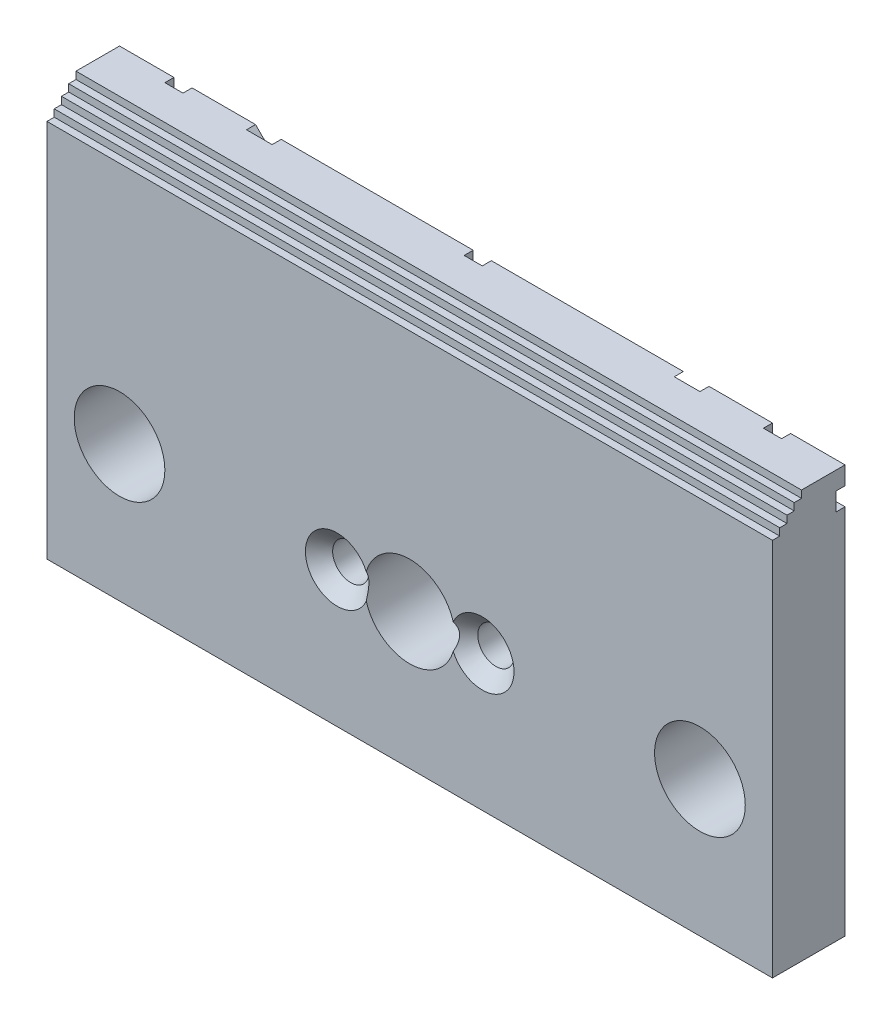
SolidWorks part; units mm, degrees
ref_plane "前视基准面" through (0, 0, 0) normal (0, 0, 1) x (1, 0, 0)
ref_plane "上视基准面" through (0, 0, 0) normal (0, 1, 0) x (1, 0, 0)
ref_plane "右视基准面" through (0, 0, 0) normal (1, 0, 0) x (0, 0, -1)
other "Configuration Table"
ref_plane "基准面1" through (0, 0, 1) normal (0, 0, -1) x (-1, 0, 0)
sketch "草图1" plane through (0, 0, 1) normal (0, 0, -1) x (-1, 0, 0)
  line L0 (-80, -13.3333) -> (0, -13.3333)
  line L1 (0, -13.3333) -> (0, 46.6667)
  line L2 (0, 46.6667) -> (-80, 46.6667)
  line L3 (-80, 46.6667) -> (-80, -13.3333)
  dimension "D1" = 80
  dimension "D2" = 60
extrude "凸台-拉伸1" add sketch "草图1" against normal blind 8
hole_wizard "Ø10.0 (10) 直径孔1" positions "草图21" profile "草图20" hole size "Ø10.0" standard "ANSI Metric" end condition through all
sketch "草图21" plane through (0, 0, 9) normal (0, 0, 1) x (1, 0, 0)
  line L0 (80, 16.6667) -> (0, 16.6667) construction
  line L1 (80, 46.6667) -> (80, -13.3333) construction
  line L2 (0, -13.3333) -> (0, 46.6667) construction
  line L3 (0, 46.6667) -> (80, 46.6667) construction
  point P0 (72, 16.6667)
  point P1 (8, 16.6667)
  dimension "D1" = 8
  dimension "D2" = 8
  dimension "D3" = 30
sketch "草图20" plane through (72, 16.6667, 9) normal (1, 0, 0) x (0, -1, 0)
  line L0 (0, 0) -> (0, 8)
  line L1 (0, 8) -> (5, 8)
  line L2 (5, 8) -> (5, 0)
  line L5 (5, 0) -> (0, 0)
  line L11 (0, -6.35) -> (0, 107.95) construction
  dimension "通孔孔直径" = 10
  dimension "通孔孔深度" = 8
hole_wizard "Ø10.0 (10) 直径孔2" positions "草图23" profile "草图22" hole size "Ø10.0" standard "ANSI Metric" end condition through all
sketch "草图23" plane through (0, 0, 1) normal (0, 0, -1) x (-1, 0, 0)
  line L0 (-80, 16.6667) -> (0, 16.6667) construction
  line L3 (0, 46.6667) -> (-80, 46.6667) construction
  point P0 (-40, 16.6667)
  dimension "D1" = 30
sketch "草图22" plane through (40, 16.6667, 1) normal (1, 0, 0) x (0, 1, 0)
  line L0 (0, 0) -> (0, 8)
  line L1 (0, 8) -> (5, 8)
  line L2 (5, 8) -> (5, 0)
  line L5 (5, 0) -> (0, 0)
  line L11 (0, -6.35) -> (0, 107.95) construction
  dimension "通孔孔直径" = 10
  dimension "通孔孔深度" = 8
hole_wizard "M3.5 平头机械螺钉的锥形沉头孔1" positions "草图25" profile "草图24" countersink size "M3.5" standard "ANSI Metric" end condition through all
sketch "草图25" plane through (0, 0, 9) normal (0, 0, 1) x (1, 0, 0)
  line L0 (0, 16.6667) -> (80, 16.6667) construction
  line L3 (0, 46.6667) -> (80, 46.6667) construction
  point P0 (32, 16.6667)
  point P1 (48, 16.6667)
  point P10 (40, 16.6667)
  dimension "D1" = 16
  dimension "D2" = 8
  dimension "D3" = 30
sketch "草图24" plane through (32, 16.6667, 9) normal (1, 0, 0) x (0, -1, 0)
  line L0 (0, 0) -> (0, 8)
  line L1 (0, 8) -> (2, 8)
  line L2 (2, 8) -> (2, 1.5)
  line L3 (2, 1.5) -> (3.5, 0)
  line L5 (3.5, 0) -> (0, 0)
  line L6 (-2, 1.5) -> (-3.5, 0) construction
  line L11 (0, -6.35) -> (0, 107.95) construction
  dimension "通孔孔直径" = 4
  dimension "通孔孔深度" = 8
  dimension "近端锥形沉头孔直径" = 7
  dimension "近端锥形沉头孔角度" = 90
sketch "草图27" plane through (0, 0, 1) normal (0, 0, -1) x (-1, 0, 0)
  line L0 (-40, 46.6667) -> (-40, -13.3333) construction
  line L1 (0, 46.6667) -> (-80, 46.6667) construction
  line L2 (-80, -13.3333) -> (0, -13.3333) construction
  line L3 (-80, 46.6667) -> (-80, -13.3333) construction
  line L4 (-80, 44.6667) -> (0, 44.6667)
  line L5 (-80, 44.6667) -> (-80, 42.6667)
  line L6 (-80, 42.6667) -> (0, 42.6667)
  line L7 (-40, 44.6667) -> (-40, 42.6667)
  line L8 (-80, 30.6667) -> (0, 30.6667) construction
  line L9 (-74, 46.6667) -> (-72, 46.6667)
  line L10 (-74, 46.6667) -> (-74, 30.6667)
  line L11 (-74, 30.6667) -> (-72, 30.6667)
  line L12 (-72, 46.6667) -> (-72, 30.6667)
  line L13 (-41, 46.6667) -> (-39, 46.6667)
  line L14 (-41, 46.6667) -> (-41, 30.6667)
  line L15 (-41, 30.6667) -> (-39, 30.6667)
  line L16 (-40, 46.6667) -> (-40, 30.6667)
  line L17 (0, -13.3333) -> (0, 46.6667) construction
  line L18 (-65, 46.6667) -> (-49, 30.6667)
  line L23 (-49, 30.6667) -> (-47.5858, 32.0809)
  line L24 (-47.5858, 32.0809) -> (-63.5858, 48.0809)
  line L25 (-63.5858, 48.0809) -> (-65, 46.6667)
  line L26 (-39, 46.6667) -> (-39, 30.6667)
  line L27 (-32.4142, 32.0809) -> (-16.4142, 48.0809)
  line L28 (-31, 30.6667) -> (-32.4142, 32.0809)
  line L29 (-15, 46.6667) -> (-31, 30.6667)
  line L30 (-16.4142, 48.0809) -> (-15, 46.6667)
  line L31 (-6, 30.6667) -> (-8, 30.6667)
  line L32 (-8, 46.6667) -> (-8, 30.6667)
  line L33 (-6, 46.6667) -> (-8, 46.6667)
  line L34 (-6, 46.6667) -> (-6, 30.6667)
  line L35 (0, 44.6667) -> (0, 42.6667)
  circle A0 centre (-73, 30.6667) radius 1
  circle A1 centre (-48.2929, 31.3738) radius 1
  circle A2 centre (-40, 30.6667) radius 1
  circle A3 centre (-31.7071, 31.3738) radius 1
  circle A4 centre (-7, 30.6667) radius 1
  line M27 (-80, 46.6667) -> (-80, -13.3333)
  line M29 (0, -13.3333) -> (0, 46.6667)
  dimension "D1" = 16
  dimension "D2" = 2
  dimension "D3" = 2
  dimension "D4" = 2
  dimension "D5" = 2
  dimension "D6" = 45
  dimension "D7" = 1
  dimension "D8" = 6
  dimension "D9" = 7
extrude "切除-拉伸1" cut sketch "草图27" against normal blind 1 contours L4 L34 L6 M29 | L32 L4 L29 L6 | L6 L27 L4 L26 | L24 L6 L14 L4 | L18 L4 L12 L6 | L10 L4 L6 M27 | A0 | A1 | A2 | A3 | A4
sketch "草图28" plane through (0, 0, 0) normal (-1, 0, 0) x (0, 0, 1)
  line L0 (9, 46.6667) -> (5.8, 46.6667)
  line L1 (9, 46.6667) -> (1, 46.6667) construction
  line L2 (5.8, 46.6667) -> (5.8, 45.8667)
  line L3 (5.8, 45.8667) -> (6.6, 45.8667)
  line L4 (6.6, 45.8667) -> (6.6, 45.0667)
  line L5 (6.6, 45.0667) -> (7.4, 45.0667)
  line L6 (7.4, 45.0667) -> (7.4, 44.2667)
  line L7 (7.4, 44.2667) -> (8.2, 44.2667)
  line L8 (8.2, 44.2667) -> (8.2, 43.4667)
  line L9 (8.2, 43.4667) -> (9, 43.4667)
  line L10 (9, -13.3333) -> (9, 46.6667) construction
  line L11 (9, 46.6667) -> (9, 43.4667)
  dimension "D1" = 0.8
  dimension "D2" = 0.8
  dimension "D3" = 0.8
  dimension "D4" = 0.8
  dimension "D5" = 0.8
  dimension "D6" = 0.8
  dimension "D7" = 0.8
  dimension "D8" = 0.8
extrude "切除-拉伸2" cut sketch "草图28" against normal up to next
sketch "草图29" plane through (0, 0, 1) normal (0, 0, -1) x (-1, 0, 0)
  line L0 (0, -13.3333) -> (0, 42.6667) construction
  line L1 (-80, -13.3333) -> (0, -13.3333)
  line L2 (-80, -13.3333) -> (-80, 1.6667)
  line L3 (-80, 1.6667) -> (0, 1.6667)
  line L4 (0, -13.3333) -> (0, 1.6667)
  dimension "D1" = 15
extrude "切除-拉伸3" cut sketch "草图29" against normal up to next
